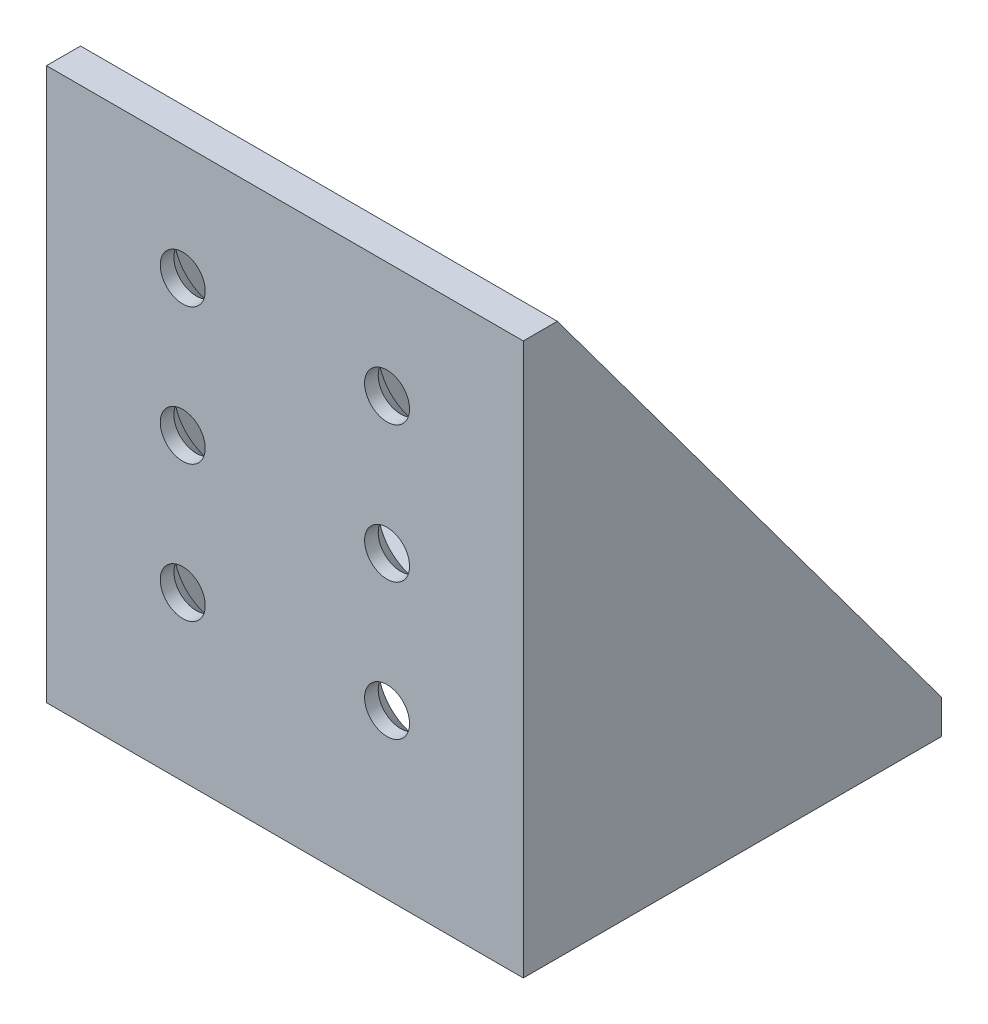
SolidWorks part; units mm, degrees
ref_plane "Płaszczyzna przednia" through (0, 0, 0) normal (0, 0, 1) x (1, 0, 0)
ref_plane "Płaszczyzna górna" through (0, 0, 0) normal (0, 1, 0) x (1, 0, 0)
ref_plane "Płaszczyzna prawa" through (0, 0, 0) normal (1, 0, 0) x (0, 0, -1)
sketch "Szkic1" plane through (0, 0, 0) normal (1, 0, 0) x (0, 0, -1)
  line L0 (0, 0) -> (61.4, 0)
  line L1 (61.4, 0) -> (61.4, 5)
  line L2 (61.4, 5) -> (5, 5)
  line L3 (5, 5) -> (5, 81)
  line L4 (5, 81) -> (0, 81)
  line L5 (0, 81) -> (0, 0)
  dimension "D1" = 5
  dimension "D2" = 5
  dimension "D3" = 76
  dimension "D4" = 56.4
extrude "Dodanie-wyciągnięcie1" add sketch "Szkic1" along normal blind 70
sketch "Szkic2" plane through (70, 0, 0) normal (1, 0, 0) x (0, 0, -1)
  line L0 (5, 81) -> (61.4, 5)
  line L1 (61.4, 5) -> (5, 5)
  line L2 (5, 5) -> (5, 81)
extrude "Dodanie-wyciągnięcie2" add sketch "Szkic2" against normal blind 6.8
ref_plane "Płaszczyzna1" through (35, 0, 0) normal (1, 0, 0) x (0, 0, -1)
mirror "Lustro1" about plane through (35, 0, 0) normal (1, 0, 0) of "Dodanie-wyciągnięcie2"
sketch "Szkic3" plane through (0, 5, 0) normal (0, 1, 0) x (1, 0, 0)
  line L0 (35, 61.4) -> (35, -0.8458) construction
  line L1 (63.2, 61.4) -> (6.8, 61.4) construction
  line L2 (35, -33.77) -> (35, 33.77) construction
  line L3 (6.8, 33.2) -> (63.2, 33.2) construction
  line L4 (6.8, 61.4) -> (6.8, 5) construction
  line L5 (63.2, 61.4) -> (63.2, 5) construction
  circle A0 centre (35, 33.2) radius 19.05
  point P14 (11.455, 57.1375)
  point P15 (58.545, 57.1375)
  point P16 (58.545, 10.0475)
  point P17 (11.455, 10.0475)
  dimension "D1" = 47.09
  dimension "D2" = 47.09
hole_wizard "Otwór gwintowany M41" positions "Szkic 3D1" profile "Szkic5" tap size "M4" standard "ISO" end condition through all
sketch3d "Szkic 3D1"
  point P0 (11.455, 5, -57.1375)
  point P3 (58.545, 5, -57.1375)
  point P6 (11.455, 5, -10.0475)
  point P9 (58.545, 5, -10.0475)
sketch "Szkic5" plane through (11.455, 5, -57.1375) normal (1, 0, 0) x (0, 0, 1)
  line L0 (0, 0) -> (0, 5)
  line L1 (0, 5) -> (1.65, 5)
  line L2 (1.65, 5) -> (1.65, 0)
  line L5 (1.65, 0) -> (0, 0)
  line L11 (0, -6.35) -> (0, 107.95) construction
  dimension "Średnica otworu gwintowanego na wylot" = 3.3
  dimension "Głębokość otworu gwintowanego na wylot" = 5
cosmetic thread "Gwint otworu1" parameters "D2"=4
cosmetic thread "Gwint otworu2" parameters "D2"=4
cosmetic thread "Gwint otworu3" parameters "D2"=4
cosmetic thread "Gwint otworu4" parameters "D2"=4
extrude "Wytnij-wyciągnięcie1" cut sketch "Szkic3" against normal blind 9.8
sketch "Szkic6" plane through (0, 0, -5) normal (0, 0, -1) x (-1, 0, 0)
  line L0 (-35, 81) -> (-35, 5) construction
  line L1 (-63.2, 81) -> (-6.8, 81) construction
  line L2 (-63.2, 5) -> (-6.8, 5) construction
  line L3 (-63.2, 76) -> (-6.8, 76) construction
  line L4 (-63.2, 5) -> (-63.2, 81) construction
  line L5 (-6.8, 81) -> (-6.8, 5) construction
  point P12 (-50, 64)
  point P13 (-20, 44)
  point P14 (-20, 24)
  point P15 (-20, 64)
  point P16 (-50, 24)
  point P17 (-50, 44)
  dimension "D1" = 5
  dimension "D2" = 12
  dimension "D3" = 40
  dimension "D4" = 20
  dimension "D5" = 30
hole_wizard "Pogłębienie stożkowe pod M6 Śrubę z łbem soczewkowym1" positions "Szkic 3D2" profile "Szkic7" countersink size "M6" standard "ISO" end condition through all
sketch3d "Szkic 3D2"
  point P0 (50, 64, -5)
  point P3 (20, 64, -5)
  point P6 (50, 44, -5)
  point P9 (20, 44, -5)
  point P12 (50, 24, -5)
  point P15 (20, 24, -5)
sketch "Szkic7" plane through (50, 64, -5) normal (1, 0, 0) x (0, 1, 0)
  line L0 (0, 0) -> (0, 5)
  line L1 (0, 5) -> (3.3, 5)
  line L2 (3.3, 5) -> (3.3, 3)
  line L3 (3.3, 3) -> (6.3, 0)
  line L5 (6.3, 0) -> (0, 0)
  line L6 (-3.3, 3) -> (-6.3, 0) construction
  line L11 (0, -6.35) -> (0, 107.95) construction
  dimension "Średnica otworu na wylot" = 6.6
  dimension "Głębokość otworu na wylot" = 5
  dimension "Średnica zewnętrznego pogłębienia stożkowego" = 12.6
  dimension "Kąt zewnętrznego pogłębienia stożkowego" = 90
